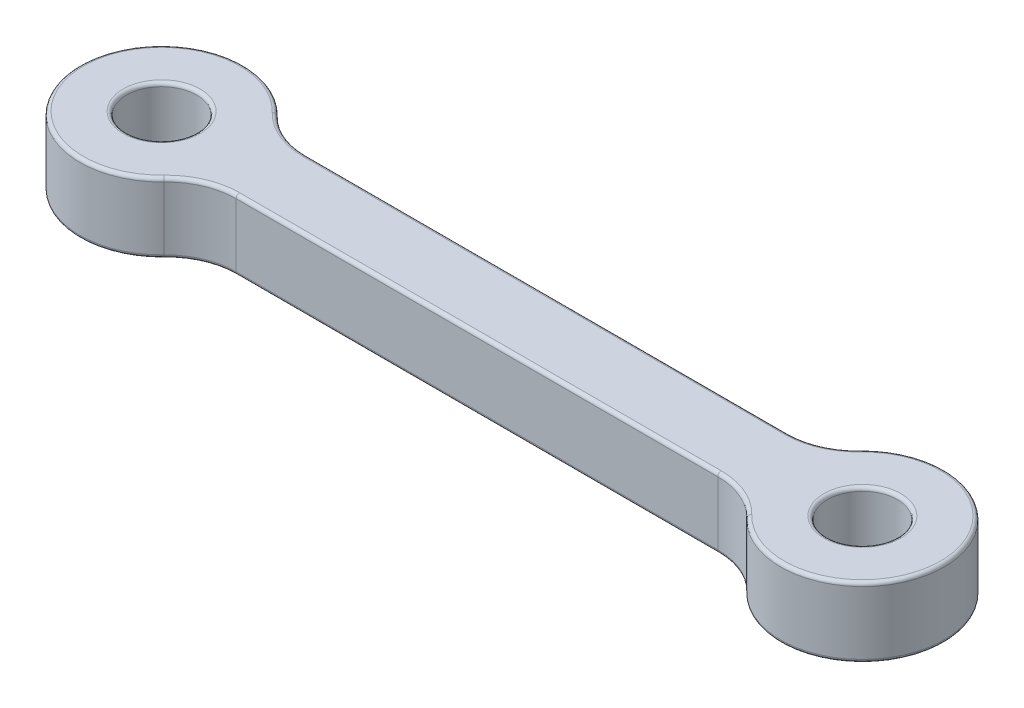
SolidWorks part; units mm, degrees
ref_plane "前视基准面" through (0, 0, 0) normal (0, 0, 1) x (1, 0, 0)
ref_plane "上视基准面" through (0, 0, 0) normal (0, 1, 0) x (1, 0, 0)
ref_plane "右视基准面" through (0, 0, 0) normal (1, 0, 0) x (0, 0, -1)
sketch "草图1" plane through (0, 0, 0) normal (0, 1, 0) x (1, 0, 0)
  line L0 (-143.1195, 0) -> (7012.855, 0) construction
  line L1 (0, -143.1195) -> (0, 7012.855) construction
  line L2 (-11.8377, 1.5) -> (11.8377, 1.5)
  line L3 (-11.8377, -1.5) -> (11.8377, -1.5)
  arc A0 (-11.8377, 1.5) -> (-11.8377, -1.5) centre (-15, 0) ccw
  circle A1 centre (-15, 0) radius 1.5
  circle A2 centre (15, 0) radius 1.5
  arc A3 (11.8377, 1.5) -> (11.8377, -1.5) centre (15, 0) cw
  point P11 (0, 1.5)
  point P15 (0, -1.5)
  dimension "D1" = 7
  dimension "D2" = 3
  dimension "D3" = 30
  dimension "D4" = 3
extrude "凸台-拉伸1" add sketch "草图1" along normal blind 3
fillet "圆角1" radius 3 4 edges at (11.8377, 1.5, 1.5) (-11.8377, 1.5, 1.5) (-11.8377, 1.5, -1.5) (11.8377, 1.5, -1.5)
fillet "圆角2" radius 0.15 19 edges at (-11.4863, 0, 1.7404) (-18.5, 0, 0) (-11.4863, 0, -1.7404) (0, 0, -1.5) (11.4863, 0, -1.7404) (18.5, 0, 0) (11.4863, 0, 1.7404) (15, 3, -1.5) (11.4863, 3, -1.7404) (18.5, 3, 0) (11.4863, 3, 1.7404) (0, 3, 1.5) (-11.4863, 3, 1.7404) (-18.5, 3, 0) (-11.4863, 3, -1.7404) (0, 3, -1.5) (-15, 3, 1.5) (15, 0, -1.5) (0, 0, 1.5)
